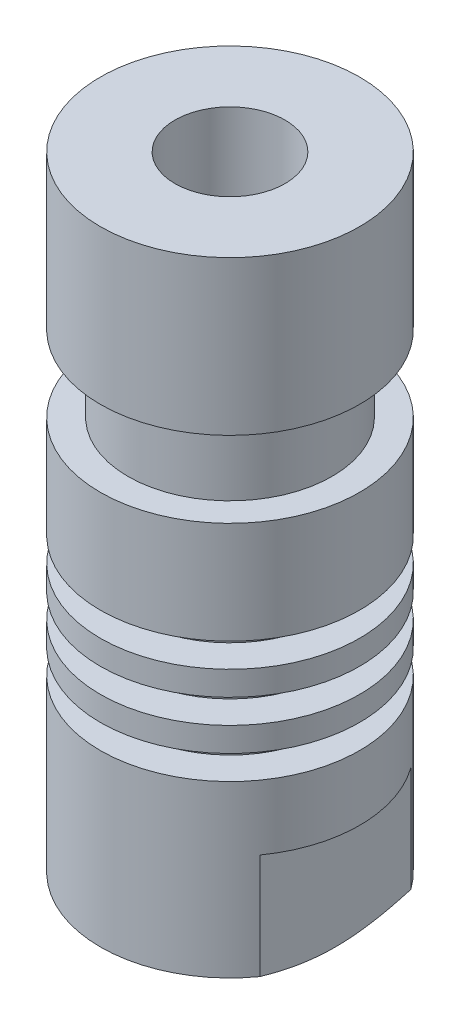
SolidWorks part; units mm, degrees
material "Gomma"
ref_plane "Piano frontale" through (0, 0, 0) normal (0, 0, 1) x (1, 0, 0)
ref_plane "Piano superiore" through (0, 0, 0) normal (0, 1, 0) x (1, 0, 0)
ref_plane "Piano destro" through (0, 0, 0) normal (1, 0, 0) x (0, 0, -1)
sketch "Schizzo1" plane through (0, 0, 0) normal (0, 0, 1) x (1, 0, 0)
  line L0 (0, 0) -> (-5, 0)
  line L1 (-5, 0) -> (-8, 1.5)
  line L2 (-8, 1.5) -> (-8, 12)
  line L3 (-8, 12) -> (-6, 12)
  line L4 (-6, 12) -> (-6, 13.5)
  line L5 (-6, 13.5) -> (-8, 13.5)
  line L6 (-8, 13.5) -> (-8, 15)
  line L7 (-8, 15) -> (-6, 15)
  line L8 (-6, 15) -> (-6, 16.5)
  line L9 (-6, 16.5) -> (-8, 16.5)
  line L10 (-8, 16.5) -> (-8, 18)
  line L11 (-8, 18) -> (-6, 18)
  line L12 (-6, 18) -> (-6, 19.5)
  line L13 (-6, 19.5) -> (-8, 19.5)
  line L14 (-8, 19.5) -> (-8, 25.8)
  line L15 (-8, 25.8) -> (-6.3, 25.8)
  line L16 (-6.3, 25.8) -> (-6.3, 30.5)
  line L17 (-6.3, 30.5) -> (-8, 30.5)
  line L18 (-8, 30.5) -> (-8, 40)
  line L19 (-8, 40) -> (0, 40)
  line L20 (0, 40) -> (0, 0)
  line L21 (0, 129.4074) -> (0, -17.2322) construction
  dimension "D1" = 1.5
  dimension "D2" = 16
  dimension "D3" = 2
  dimension "D4" = 40
  dimension "D5" = 12
  dimension "D6" = 9.5
  dimension "D7" = 4.7
  dimension "D8" = 1.5
  dimension "D9" = 1.7
  dimension "D10" = 10
revolve "Rivoluzione1" add sketch "Schizzo1" angle 360 about L21
sketch "Schizzo2" plane through (0, 0, 0) normal (0, 0, 1) x (1, 0, 0)
  line L0 (-8, 8) -> (-6.5, 8)
  line L1 (-6.5, 8) -> (-6.5, 0)
  line L2 (-6.5, 0) -> (-8, 0)
  line L3 (-8, 0) -> (-8, 8)
  line L4 (6.5, 8) -> (6.5, 0)
  line L5 (6.5, 0) -> (8, 0)
  line L6 (8, 0) -> (8, 8)
  line L7 (8, 8) -> (6.5, 8)
  line L8 (0, 0) -> (0, 9.0399) construction
  line L9 (-5, 0) -> (5, 0) construction
  line L10 (8, 40) -> (-8, 40) construction
  line L11 (8, 1.5) -> (8, 12) construction
  line L12 (-8, 12) -> (-8, 1.5) construction
  dimension "D1" = 32
  dimension "D2" = 1.5
extrude "Taglio-Estrusione1" cut sketch "Schizzo2" against normal up to next and the other way up to next
hole_wizard "Foro filettato M8-1" positions "Schizzo5" profile "Schizzo6" tap size "M8" standard "ISO" end condition through all
sketch "Schizzo5" plane through (0, 40, 0) normal (0, 1, 0) x (1, 0, 0)
  point P0 (0, 0)
sketch "Schizzo6" plane through (0, 40, 0) normal (1, 0, 0) x (0, 0, 1)
  line L0 (0, 0) -> (0, 40)
  line L1 (0, 40) -> (3.4, 40)
  line L2 (3.4, 40) -> (3.4, 0)
  line L5 (3.4, 0) -> (0, 0)
  line L11 (0, -6.35) -> (0, 107.95) construction
  dimension "Thru Tap Drill Dia." = 6.8
  dimension "Thru Tap Drill Depth" = 40
cosmetic thread "Filettatura del foro1" parameters "D2"=8
